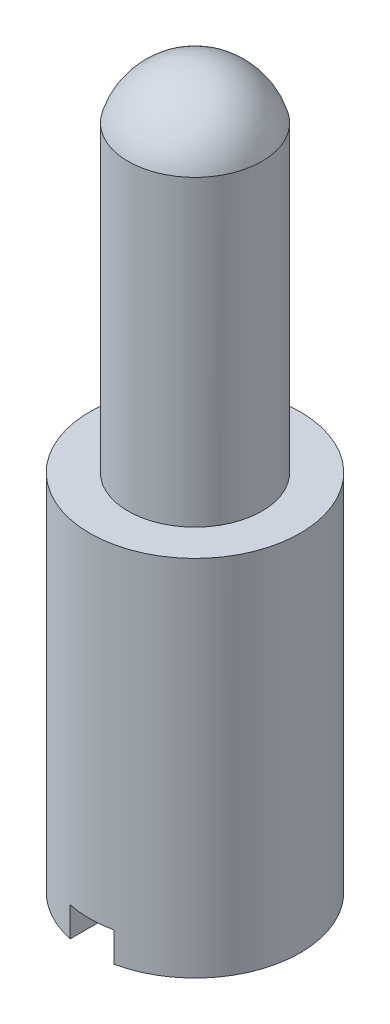
SolidWorks part; units mm, degrees
ref_plane "Front Plane" through (0, 0, 0) normal (0, 0, 1) x (1, 0, 0)
ref_plane "Top Plane" through (0, 0, 0) normal (0, 1, 0) x (1, 0, 0)
ref_plane "Right Plane" through (0, 0, 0) normal (1, 0, 0) x (0, 0, -1)
sketch "Sketch1" plane through (0, 0, 0) normal (0, 0, 1) x (1, 0, 0)
  line L0 (0, 0) -> (0, 19.05)
  line L1 (0, 0) -> (2.794, 0)
  line L2 (2.794, 0) -> (2.794, 9.652)
  line L3 (2.794, 9.652) -> (1.778, 9.652)
  line L4 (1.778, 9.652) -> (1.778, 17.6965)
  arc A0 (1.778, 17.6965) -> (0, 19.05) centre (0, 17.2054) ccw
  point P8 (0, 0)
  dimension "D1" = 19.05
  dimension "D2" = 2.794
  dimension "D3" = 9.652
  dimension "D4" = 1.778
revolve "Revolve1" add sketch "Sketch1" angle 360 about L0
cosmetic thread "Cosmetic Thread1" parameters "D2"=4.2266
sketch "Sketch2" plane through (0, 0, 0) normal (0, 0, 1) x (1, 0, 0)
  line L0 (-2.794, 0) -> (2.794, 0) construction
  line L1 (-0.5842, 0) -> (0.5842, 0)
  line L2 (-0.5842, 0) -> (-0.5842, 0.7874)
  line L3 (-0.5842, 0.7874) -> (0.5842, 0.7874)
  line L4 (0.5842, 0) -> (0.5842, 0.7874)
  dimension "D1" = 0.7874
  dimension "D2" = 1.1684
extrude "Cut-Extrude1" cut sketch "Sketch2" against normal through all both and the other way through all
